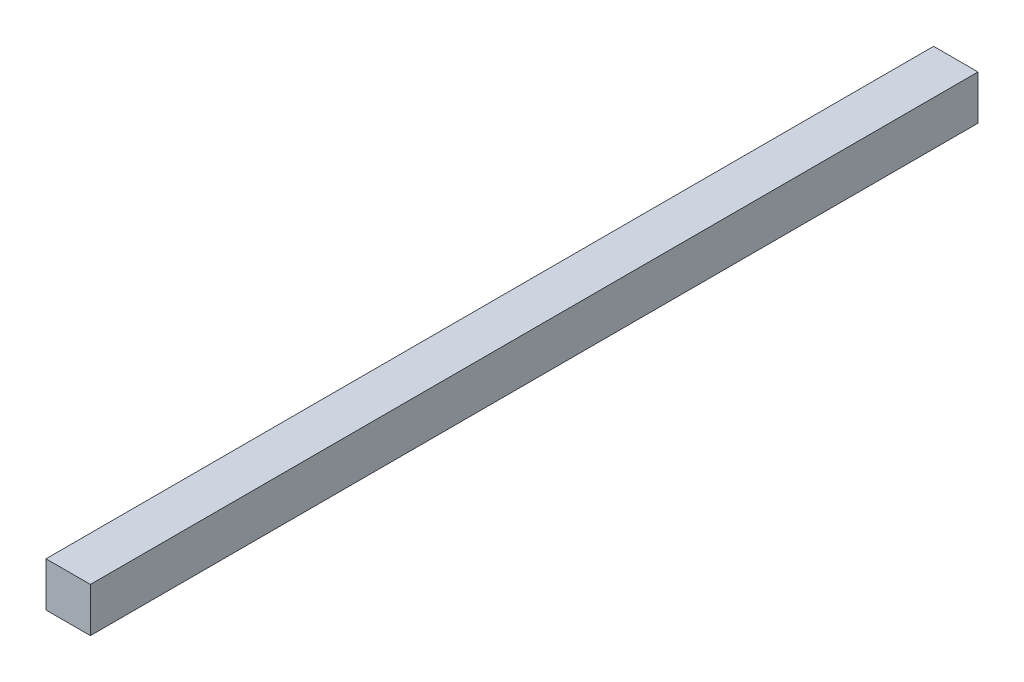
SolidWorks part; units mm, degrees
ref_plane "Front Plane" through (0, 0, 0) normal (0, 0, 1) x (1, 0, 0)
ref_plane "Top Plane" through (0, 0, 0) normal (0, 1, 0) x (1, 0, 0)
ref_plane "Right Plane" through (0, 0, 0) normal (1, 0, 0) x (0, 0, -1)
sketch "Sketch1" plane through (0, 0, 0) normal (0, 0, 1) x (1, 0, 0)
  line L1 (0, 0) -> (-15.24, 0)
  line L2 (0, 0) -> (0, 15.24)
  line L3 (0, 15.24) -> (-15.24, 15.24)
  line L4 (-15.24, 0) -> (-15.24, 15.24)
  dimension "D1" = 15.24
  dimension "D2" = 15.24
extrude "Boss-Extrude1" add sketch "Sketch1" along normal blind 304.8
